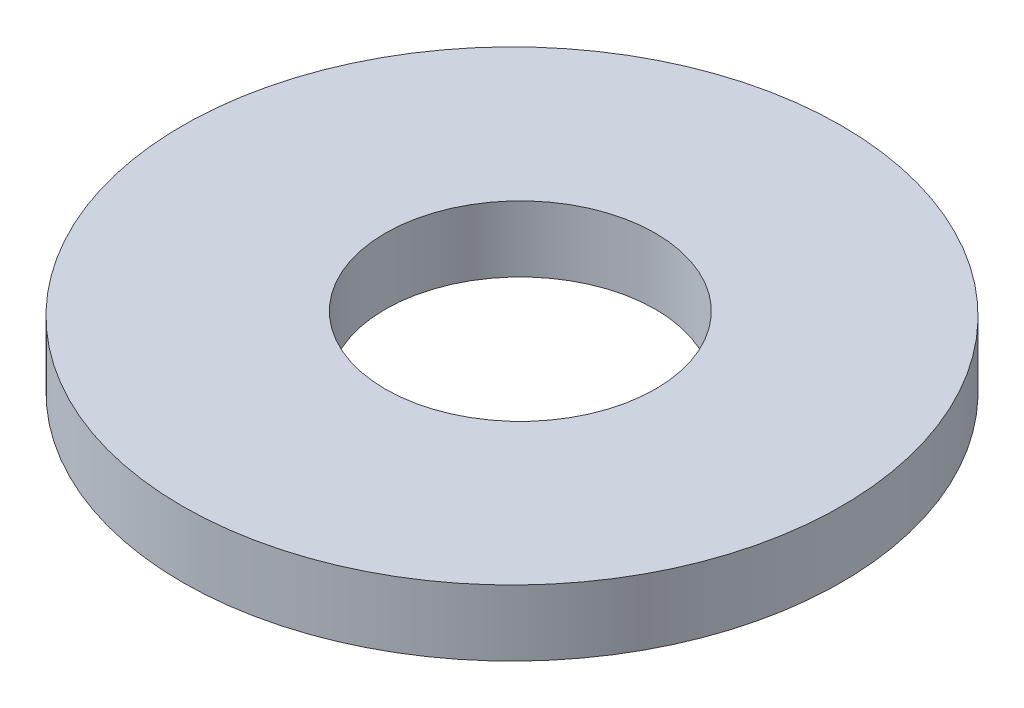
SolidWorks part; units mm, degrees
ref_plane "Front Plane" through (0, 0, 0) normal (0, 0, 1) x (1, 0, 0)
ref_plane "Top Plane" through (0, 0, 0) normal (0, 1, 0) x (1, 0, 0)
ref_plane "Right Plane" through (0, 0, 0) normal (1, 0, 0) x (0, 0, -1)
sketch "Sketch1" plane through (0, 0, 0) normal (0, 1, 0) x (1, 0, 0)
  circle A0 centre (0, 0) radius 50
  dimension "D1" = 100
extrude "Boss-Extrude1" add sketch "Sketch1" along normal blind 10
sketch "Sketch2" plane through (0, 10, 0) normal (0, 1, 0) x (1, 0, 0)
  circle A0 centre (0, 1.2656) radius 20.4924
extrude "Cut-Extrude1" cut sketch "Sketch2" against normal through all
